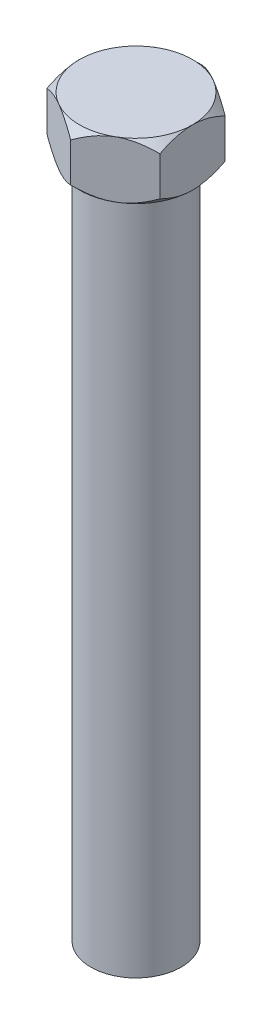
SolidWorks part; units mm, degrees
ref_plane "Alzado" through (0, 0, 0) normal (0, 0, 1) x (1, 0, 0)
ref_plane "Planta" through (0, 0, 0) normal (0, 1, 0) x (1, 0, 0)
ref_plane "Vista lateral" through (0, 0, 0) normal (1, 0, 0) x (0, 0, -1)
sketch "Croquis1" plane through (0, 0, 0) normal (0, 1, 0) x (1, 0, 0)
  line L1 (0, -5.7735) -> (5, -2.8868)
  line L2 (5, -2.8868) -> (5, 2.8868)
  line L3 (5, 2.8868) -> (0, 5.7735)
  line L4 (0, 5.7735) -> (-5, 2.8868)
  line L5 (-5, 2.8868) -> (-5, -2.8868)
  line L6 (-5, -2.8868) -> (0, -5.7735)
  circle A0 centre (0, 0) radius 5 construction
  dimension "D1" = 10
extrude "Saliente-Extruir1" add sketch "Croquis1" along normal mid plane 5
sketch "Croquis3" plane through (0, -2.5, 0) normal (0, -1, 0) x (1, 0, 0)
  circle A0 centre (0, 0) radius 4
  dimension "D1" = 8
extrude "Saliente-Extruir3" add sketch "Croquis3" along normal blind 60
sketch "Croquis4" plane through (0, -2.5, 0) normal (0, -1, 0) x (1, 0, 0)
  circle A0 centre (0, 0) radius 5
  dimension "D1" = 10
extrude "Cortar-Extruir1" cut sketch "Croquis4" against normal blind 30 draft 45 flip side to cut
mirror "Simetría1" about plane through (0, 0, 0) normal (0, 1, 0) of "Cortar-Extruir1"
